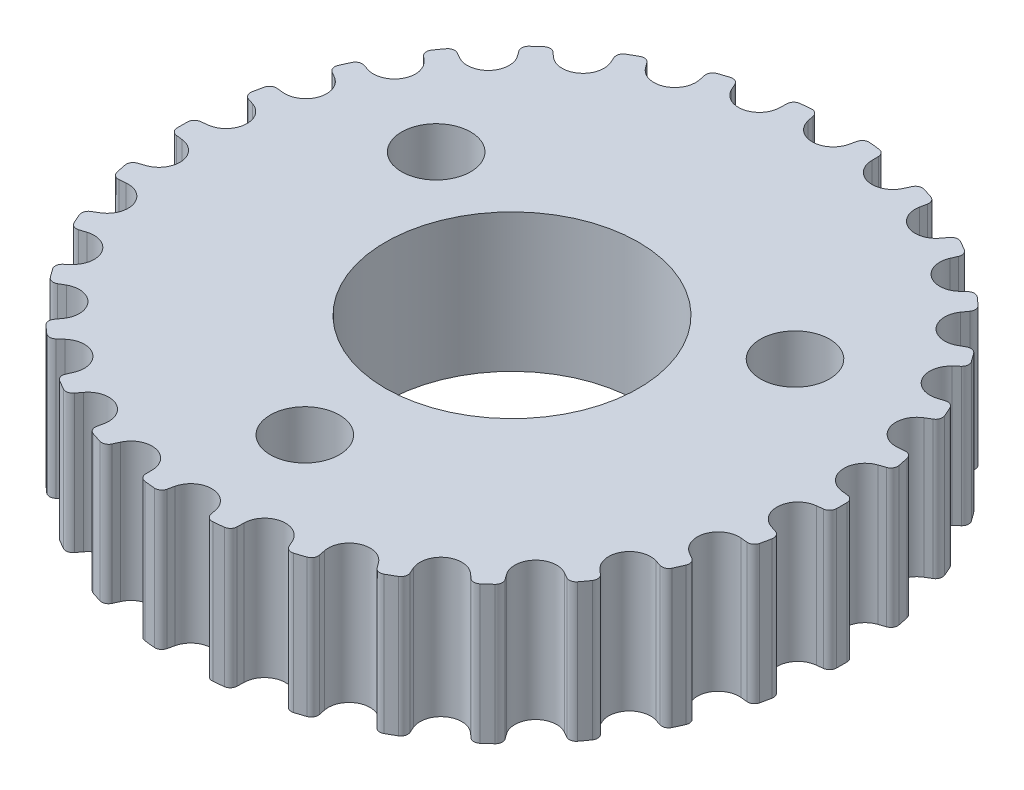
SolidWorks part; units mm, degrees
material "Acrylic (Medium-high impact)"
ref_plane "Front Plane" through (0, 0, 0) normal (0, 0, 1) x (1, 0, 0)
ref_plane "Top Plane" through (0, 0, 0) normal (0, 1, 0) x (1, 0, 0)
ref_plane "Right Plane" through (0, 0, 0) normal (1, 0, 0) x (0, 0, -1)
sketch "Sketch1" plane through (0, 0, 0) normal (0, 1, 0) x (1, 0, 0)
  circle A0 centre (0, 0) radius 14.3239
  dimension "D1" = 28.6479
extrude "Boss-Extrude1" add sketch "Sketch1" along normal blind 6
sketch "Sketch2" plane through (0, 6, 0) normal (0, 1, 0) x (1, 0, 0)
  line L0 (0, 0) -> (0, 14.3239) construction
  line L1 (-0.8883, 13.7564) -> (-0.95, 14.0339)
  line L2 (-2.9781, 14.0109) -> (-2.9781, 14.3239)
  line L3 (-2.9781, 14.3239) -> (2.9781, 14.3239)
  line L4 (0.8883, 13.7564) -> (0.95, 14.0339)
  line L5 (2.9781, 14.0109) -> (2.9781, 14.3239)
  circle A0 centre (0, 0) radius 14.3239 construction
  arc A1 (0.8883, 13.7564) -> (-0.8883, 13.7564) centre (0, 13.9539) cw
  arc A2 (-0.95, 14.0339) -> (-1.2694, 14.2676) centre (-1.2428, 13.9688) ccw
  arc A4 (0.95, 14.0339) -> (1.2694, 14.2676) centre (1.2428, 13.9688) cw
  arc A5 (-1.2694, 14.2676) -> (-2.9781, 14.0109) centre (0, 0) ccw
  arc A6 (1.2694, 14.2676) -> (2.9781, 14.0109) centre (0, 0) cw
  circle A8 centre (0, 0) radius 14.3239 construction
  point P11 (0, 14.3239)
  point P19 (0, 13.0439)
  dimension "D3" = 0.3
  dimension "D5" = 0.91
  dimension "D2" = 0.95
  dimension "D4" = 1.28
  dimension "D6" = 12
extrude "Cut-Extrude1" cut sketch "Sketch2" against normal through all
pattern_circular "CirPattern1" count 30 over 360 about axis through (0, 0, 0) along (0, 1, 0) of "Cut-Extrude1"
sketch "Sketch3" plane through (0, 0, 0) normal (0, -1, 0) x (1, 0, 0)
  circle A0 centre (0, 0) radius 5.5
  dimension "D1" = 11
extrude "Cut-Extrude2" cut sketch "Sketch3" against normal through all
sketch "Sketch4" plane through (0, 0, 0) normal (0, -1, 0) x (1, 0, 0)
  line L0 (0, 0) -> (0, 9) construction
  circle A0 centre (0, 9) radius 1.5
  circle A1 centre (7.7942, -4.5) radius 1.5
  circle A2 centre (-7.7942, -4.5) radius 1.5
  point P14 (0, 0)
  dimension "D1" = 3
  dimension "D2" = 9
  dimension "D3" = 3
extrude "Cut-Extrude3" cut sketch "Sketch4" against normal through all
sketch "Sketch5" plane through (0, 0, 0) normal (0, -1, 0) x (1, 0, 0)
  line L60 (8.7383, -10.682) -> (8.9513, -10.8702)
  line L61 (8.7383, -10.682) -> (8.9513, -10.8702)
  line L62 (9.875, -10.0385) -> (9.7101, -9.807)
  line L63 (9.875, -10.0385) -> (9.7101, -9.807)
  line L64 (12.5987, 6.2896) -> (12.3276, 6.2043)
  line L65 (12.5987, 6.2896) -> (12.3276, 6.2043)
  line L66 (11.5369, 7.5738) -> (11.7463, 7.766)
  line L67 (11.5369, 7.5738) -> (11.7463, 7.766)
  line L68 (-3.638, 13.3126) -> (-3.7561, 13.5712)
  line L69 (-3.638, 13.3126) -> (-3.7561, 13.5712)
  line L70 (-4.9382, 13.1871) -> (-4.8817, 12.9085)
  line L71 (-4.9382, 13.1871) -> (-4.8817, 12.9085)
  line L72 (-11.7463, 7.766) -> (-11.5369, 7.5738)
  line L73 (-11.7463, 7.766) -> (-11.5369, 7.5738)
  line L74 (-12.3276, 6.2043) -> (-12.5987, 6.2896)
  line L75 (-12.3276, 6.2043) -> (-12.5987, 6.2896)
  line L76 (-13.1043, 5.1541) -> (-12.8594, 5.0097)
  line L77 (-13.1043, 5.1541) -> (-12.8594, 5.0097)
  line L78 (-13.3481, 3.5057) -> (-13.6311, 3.5327)
  line L79 (-13.3481, 3.5057) -> (-13.6311, 3.5327)
  line L80 (-13.8895, 2.3169) -> (-13.62, 2.2266)
  line L81 (-13.8895, 2.3169) -> (-13.62, 2.2266)
  line L82 (-13.7853, 0.6538) -> (-14.0677, 0.6215)
  line L83 (-13.7853, 0.6538) -> (-14.0677, 0.6215)
  line L84 (-14.0677, -0.6215) -> (-13.7853, -0.6538)
  line L85 (-14.0677, -0.6215) -> (-13.7853, -0.6538)
  line L86 (-13.62, -2.2266) -> (-13.8895, -2.3169)
  line L87 (-13.62, -2.2266) -> (-13.8895, -2.3169)
  line L88 (-13.6311, -3.5327) -> (-13.3481, -3.5057)
  line L89 (-13.6311, -3.5327) -> (-13.3481, -3.5057)
  line L90 (-12.8594, -5.0097) -> (-13.1043, -5.1541)
  line L91 (-12.8594, -5.0097) -> (-13.1043, -5.1541)
  line L92 (-12.5987, -6.2896) -> (-12.3276, -6.2043)
  line L93 (-12.5987, -6.2896) -> (-12.3276, -6.2043)
  line L94 (-11.5369, -7.5738) -> (-11.7463, -7.766)
  line L95 (-11.5369, -7.5738) -> (-11.7463, -7.766)
  line L96 (-11.0157, -8.7716) -> (-10.7682, -8.6318)
  line L97 (-11.0157, -8.7716) -> (-10.7682, -8.6318)
  line L98 (-9.7101, -9.807) -> (-9.875, -10.0385)
  line L99 (-9.7101, -9.807) -> (-9.875, -10.0385)
  line L100 (-8.9513, -10.8702) -> (-8.7383, -10.682)
  line L101 (-8.9513, -10.8702) -> (-8.7383, -10.682)
  line L102 (-7.4589, -11.6115) -> (-7.5721, -11.8722)
  line L103 (-7.4589, -11.6115) -> (-7.5721, -11.8722)
  line L104 (-6.4956, -12.4937) -> (-6.3264, -12.2653)
  line L105 (-6.4956, -12.4937) -> (-6.3264, -12.2653)
  line L106 (-4.8817, -12.9085) -> (-4.9382, -13.1871)
  line L107 (-4.8817, -12.9085) -> (-4.9382, -13.1871)
  line L108 (-3.7561, -13.5712) -> (-3.638, -13.3126)
  line L109 (-3.7561, -13.5712) -> (-3.638, -13.3126)
  line L110 (-2.0912, -13.6414) -> (-2.0886, -13.9257)
  line L111 (-2.0912, -13.6414) -> (-2.0886, -13.9257)
  line L120 (6.3264, -12.2653) -> (6.4956, -12.4937)
  line L121 (7.5721, -11.8722) -> (7.4589, -11.6115)
  line L124 (10.7682, -8.6318) -> (11.0157, -8.7716)
  line L125 (11.7463, -7.766) -> (11.5369, -7.5738)
  line L126 (12.3276, -6.2043) -> (12.5987, -6.2896)
  line L127 (13.1043, -5.1541) -> (12.8594, -5.0097)
  line L128 (13.3481, -3.5057) -> (13.6311, -3.5327)
  line L129 (13.8895, -2.3169) -> (13.62, -2.2266)
  line L130 (13.7853, -0.6538) -> (14.0677, -0.6215)
  line L131 (14.0677, 0.6215) -> (13.7853, 0.6538)
  line L132 (13.62, 2.2266) -> (13.8895, 2.3169)
  line L133 (13.6311, 3.5327) -> (13.3481, 3.5057)
  line L134 (12.8594, 5.0097) -> (13.1043, 5.1541)
  line L137 (11.0157, 8.7716) -> (10.7682, 8.6318)
  line L138 (9.7101, 9.807) -> (9.875, 10.0385)
  line L139 (8.9513, 10.8702) -> (8.7383, 10.682)
  line L140 (7.4589, 11.6115) -> (7.5721, 11.8722)
  line L141 (6.4956, 12.4937) -> (6.3264, 12.2653)
  line L142 (4.8817, 12.9085) -> (4.9382, 13.1871)
  line L143 (3.7561, 13.5712) -> (3.638, 13.3126)
  line L144 (2.0912, 13.6414) -> (2.0886, 13.9257)
  line L145 (0.8524, 14.0556) -> (0.7907, 13.7781)
  line L146 (-0.7907, 13.7781) -> (-0.8524, 14.0556)
  line L147 (-2.0886, 13.9257) -> (-2.0912, 13.6414)
  line L150 (-6.3264, 12.2653) -> (-6.4956, 12.4937)
  line L151 (-7.5721, 11.8722) -> (-7.4589, 11.6115)
  line L152 (-8.7383, 10.682) -> (-8.9513, 10.8702)
  line L153 (-9.875, 10.0385) -> (-9.7101, 9.807)
  line L154 (-10.7682, 8.6318) -> (-11.0157, 8.7716)
  line L175 (-0.8524, -14.0556) -> (-0.7907, -13.7781)
  line L176 (0.7907, -13.7781) -> (0.8524, -14.0556)
  line L177 (2.0886, -13.9257) -> (2.0912, -13.6414)
  line L178 (3.638, -13.3126) -> (3.7561, -13.5712)
  line L179 (4.9382, -13.1871) -> (4.8817, -12.9085)
  line L180 (6.3264, -12.2653) -> (6.4956, -12.4937)
  line L181 (7.5721, -11.8722) -> (7.4589, -11.6115)
  line L184 (10.7682, -8.6318) -> (11.0157, -8.7716)
  line L185 (11.7463, -7.766) -> (11.5369, -7.5738)
  line L186 (12.3276, -6.2043) -> (12.5987, -6.2896)
  line L187 (13.1043, -5.1541) -> (12.8594, -5.0097)
  line L188 (13.3481, -3.5057) -> (13.6311, -3.5327)
  line L189 (13.8895, -2.3169) -> (13.62, -2.2266)
  line L190 (13.7853, -0.6538) -> (14.0677, -0.6215)
  line L191 (14.0677, 0.6215) -> (13.7853, 0.6538)
  line L192 (13.62, 2.2266) -> (13.8895, 2.3169)
  line L193 (13.6311, 3.5327) -> (13.3481, 3.5057)
  line L194 (12.8594, 5.0097) -> (13.1043, 5.1541)
  line L197 (11.0157, 8.7716) -> (10.7682, 8.6318)
  line L198 (9.7101, 9.807) -> (9.875, 10.0385)
  line L199 (8.9513, 10.8702) -> (8.7383, 10.682)
  line L200 (7.4589, 11.6115) -> (7.5721, 11.8722)
  line L201 (6.4956, 12.4937) -> (6.3264, 12.2653)
  line L202 (4.8817, 12.9085) -> (4.9382, 13.1871)
  line L203 (3.7561, 13.5712) -> (3.638, 13.3126)
  line L204 (2.0912, 13.6414) -> (2.0886, 13.9257)
  line L205 (0.8524, 14.0556) -> (0.7907, 13.7781)
  line L206 (-0.7907, 13.7781) -> (-0.8524, 14.0556)
  line L207 (-2.0886, 13.9257) -> (-2.0912, 13.6414)
  line L210 (-6.3264, 12.2653) -> (-6.4956, 12.4937)
  line L211 (-7.5721, 11.8722) -> (-7.4589, 11.6115)
  line L212 (-8.7383, 10.682) -> (-8.9513, 10.8702)
  line L213 (-9.875, 10.0385) -> (-9.7101, 9.807)
  line L214 (-10.7682, 8.6318) -> (-11.0157, 8.7716)
  line L235 (-0.8524, -14.0556) -> (-0.7907, -13.7781)
  line L236 (0.7907, -13.7781) -> (0.8524, -14.0556)
  line L237 (2.0886, -13.9257) -> (2.0912, -13.6414)
  line L238 (3.638, -13.3126) -> (3.7561, -13.5712)
  line L239 (4.9382, -13.1871) -> (4.8817, -12.9085)
  arc A76 (8.9513, -10.8702) -> (9.479, -10.8719) centre (9.2161, -10.5704) ccw
  arc A77 (8.9513, -10.8702) -> (9.479, -10.8719) centre (9.2161, -10.5704) ccw
  arc A78 (9.479, -10.8719) -> (9.8216, -10.5635) centre (0, 0) ccw
  arc A79 (9.479, -10.8719) -> (9.8216, -10.5635) centre (0, 0) ccw
  arc A80 (9.8216, -10.5635) -> (9.875, -10.0385) centre (9.5492, -10.2705) ccw
  arc A81 (9.8216, -10.5635) -> (9.875, -10.0385) centre (9.5492, -10.2705) ccw
  circle A120 centre (0, 0) radius 13.0439
  arc A121 (-0.8883, 13.7564) -> (0.8883, 13.7564) centre (0, 13.9539) ccw construction
  arc A128 (11.5369, 7.5738) -> (12.3276, 6.2043) centre (12.0845, 6.977) ccw
  arc A129 (11.5369, 7.5738) -> (12.3276, 6.2043) centre (12.0845, 6.977) ccw
  arc A130 (-3.7561, 13.5712) -> (-4.2375, 13.7875) centre (-4.12, 13.4051) ccw
  arc A131 (-3.7561, 13.5712) -> (-4.2375, 13.7875) centre (-4.12, 13.4051) ccw
  arc A132 (-4.2375, 13.7875) -> (-4.6759, 13.645) centre (0, 0) ccw
  arc A133 (-4.2375, 13.7875) -> (-4.6759, 13.645) centre (0, 0) ccw
  arc A134 (-4.6759, 13.645) -> (-4.9382, 13.1871) centre (-4.5462, 13.2666) ccw
  arc A135 (-4.6759, 13.645) -> (-4.9382, 13.1871) centre (-4.5462, 13.2666) ccw
  arc A136 (-11.8032, 8.2906) -> (-11.7463, 7.766) centre (-11.4759, 8.0607) ccw
  arc A137 (-11.8032, 8.2906) -> (-11.7463, 7.766) centre (-11.4759, 8.0607) ccw
  arc A138 (-12.3276, 6.2043) -> (-11.5369, 7.5738) centre (-12.0845, 6.977) ccw
  arc A139 (-12.3276, 6.2043) -> (-11.5369, 7.5738) centre (-12.0845, 6.977) ccw
  arc A140 (-12.5987, 6.2896) -> (-13.0815, 6.0766) centre (-12.7187, 5.908) ccw
  arc A141 (-12.5987, 6.2896) -> (-13.0815, 6.0766) centre (-12.7187, 5.908) ccw
  arc A142 (-13.0815, 6.0766) -> (-13.269, 5.6554) centre (0, 0) ccw
  arc A143 (-13.0815, 6.0766) -> (-13.269, 5.6554) centre (0, 0) ccw
  arc A144 (-13.269, 5.6554) -> (-13.1043, 5.1541) centre (-12.901, 5.4986) ccw
  arc A145 (-13.269, 5.6554) -> (-13.1043, 5.1541) centre (-12.901, 5.4986) ccw
  arc A146 (-13.3481, 3.5057) -> (-12.8594, 5.0097) centre (-13.271, 4.312) ccw
  arc A147 (-13.3481, 3.5057) -> (-12.8594, 5.0097) centre (-13.271, 4.312) ccw
  arc A148 (-13.6311, 3.5327) -> (-14.059, 3.224) centre (-13.6691, 3.1346) ccw
  arc A149 (-13.6311, 3.5327) -> (-14.059, 3.224) centre (-13.6691, 3.1346) ccw
  arc A150 (-14.059, 3.224) -> (-14.1549, 2.7731) centre (0, 0) ccw
  arc A151 (-14.059, 3.224) -> (-14.1549, 2.7731) centre (0, 0) ccw
  arc A152 (-14.1549, 2.7731) -> (-13.8895, 2.3169) centre (-13.7623, 2.6962) ccw
  arc A153 (-14.1549, 2.7731) -> (-13.8895, 2.3169) centre (-13.7623, 2.6962) ccw
  arc A154 (-13.7853, 0.6538) -> (-13.62, 2.2266) centre (-13.8775, 1.4586) ccw
  arc A155 (-13.7853, 0.6538) -> (-13.62, 2.2266) centre (-13.8775, 1.4586) ccw
  arc A156 (-14.0677, 0.6215) -> (-14.4221, 0.2305) centre (-14.0222, 0.2241) ccw
  arc A157 (-14.0677, 0.6215) -> (-14.4221, 0.2305) centre (-14.0222, 0.2241) ccw
  arc A158 (-14.4221, 0.2305) -> (-14.4221, -0.2305) centre (0, 0) ccw
  arc A159 (-14.4221, 0.2305) -> (-14.4221, -0.2305) centre (0, 0) ccw
  arc A160 (-14.4221, -0.2305) -> (-14.0677, -0.6215) centre (-14.0222, -0.2241) ccw
  arc A161 (-14.4221, -0.2305) -> (-14.0677, -0.6215) centre (-14.0222, -0.2241) ccw
  arc A162 (-13.62, -2.2266) -> (-13.7853, -0.6538) centre (-13.8775, -1.4586) ccw
  arc A163 (-13.62, -2.2266) -> (-13.7853, -0.6538) centre (-13.8775, -1.4586) ccw
  arc A164 (-13.8895, -2.3169) -> (-14.1549, -2.7731) centre (-13.7623, -2.6962) ccw
  arc A165 (-13.8895, -2.3169) -> (-14.1549, -2.7731) centre (-13.7623, -2.6962) ccw
  arc A166 (-14.1549, -2.7731) -> (-14.059, -3.224) centre (0, 0) ccw
  arc A167 (-14.1549, -2.7731) -> (-14.059, -3.224) centre (0, 0) ccw
  arc A168 (-14.059, -3.224) -> (-13.6311, -3.5327) centre (-13.6691, -3.1346) ccw
  arc A169 (-14.059, -3.224) -> (-13.6311, -3.5327) centre (-13.6691, -3.1346) ccw
  arc A170 (-12.8594, -5.0097) -> (-13.3481, -3.5057) centre (-13.271, -4.312) ccw
  arc A171 (-12.8594, -5.0097) -> (-13.3481, -3.5057) centre (-13.271, -4.312) ccw
  arc A172 (-13.1043, -5.1541) -> (-13.269, -5.6554) centre (-12.901, -5.4986) ccw
  arc A173 (-13.1043, -5.1541) -> (-13.269, -5.6554) centre (-12.901, -5.4986) ccw
  arc A174 (-13.269, -5.6554) -> (-13.0815, -6.0766) centre (0, 0) ccw
  arc A175 (-13.269, -5.6554) -> (-13.0815, -6.0766) centre (0, 0) ccw
  arc A176 (-13.0815, -6.0766) -> (-12.5987, -6.2896) centre (-12.7187, -5.908) ccw
  arc A177 (-13.0815, -6.0766) -> (-12.5987, -6.2896) centre (-12.7187, -5.908) ccw
  arc A178 (-11.5369, -7.5738) -> (-12.3276, -6.2043) centre (-12.0845, -6.977) ccw
  arc A179 (-11.5369, -7.5738) -> (-12.3276, -6.2043) centre (-12.0845, -6.977) ccw
  arc A180 (-11.7463, -7.766) -> (-11.8032, -8.2906) centre (-11.4759, -8.0607) ccw
  arc A181 (-11.7463, -7.766) -> (-11.8032, -8.2906) centre (-11.4759, -8.0607) ccw
  arc A182 (-11.8032, -8.2906) -> (-11.5323, -8.6636) centre (0, 0) ccw
  arc A183 (-11.8032, -8.2906) -> (-11.5323, -8.6636) centre (0, 0) ccw
  arc A184 (-11.5323, -8.6636) -> (-11.0157, -8.7716) centre (-11.2124, -8.4233) ccw
  arc A185 (-11.5323, -8.6636) -> (-11.0157, -8.7716) centre (-11.2124, -8.4233) ccw
  arc A186 (-9.7101, -9.807) -> (-10.7682, -8.6318) centre (-10.3698, -9.337) ccw
  arc A187 (-9.7101, -9.807) -> (-10.7682, -8.6318) centre (-10.3698, -9.337) ccw
  arc A188 (-9.875, -10.0385) -> (-9.8216, -10.5635) centre (-9.5492, -10.2705) ccw
  arc A189 (-9.875, -10.0385) -> (-9.8216, -10.5635) centre (-9.5492, -10.2705) ccw
  arc A190 (-9.8216, -10.5635) -> (-9.479, -10.8719) centre (0, 0) ccw
  arc A191 (-9.8216, -10.5635) -> (-9.479, -10.8719) centre (0, 0) ccw
  arc A192 (-9.479, -10.8719) -> (-8.9513, -10.8702) centre (-9.2161, -10.5704) ccw
  arc A193 (-9.479, -10.8719) -> (-8.9513, -10.8702) centre (-9.2161, -10.5704) ccw
  arc A194 (-7.4589, -11.6115) -> (-8.7383, -10.682) centre (-8.2019, -11.289) ccw
  arc A195 (-7.4589, -11.6115) -> (-8.7383, -10.682) centre (-8.2019, -11.289) ccw
  arc A196 (-7.5721, -11.8722) -> (-7.4107, -12.3747) centre (-7.2051, -12.0315) ccw
  arc A197 (-7.5721, -11.8722) -> (-7.4107, -12.3747) centre (-7.2051, -12.0315) ccw
  arc A198 (-7.4107, -12.3747) -> (-7.0114, -12.6052) centre (0, 0) ccw
  arc A199 (-7.4107, -12.3747) -> (-7.0114, -12.6052) centre (0, 0) ccw
  arc A200 (-7.0114, -12.6052) -> (-6.4956, -12.4937) centre (-6.817, -12.2556) ccw
  arc A201 (-7.0114, -12.6052) -> (-6.4956, -12.4937) centre (-6.817, -12.2556) ccw
  arc A202 (-4.8817, -12.9085) -> (-6.3264, -12.2653) centre (-5.6756, -12.7476) ccw
  arc A203 (-4.8817, -12.9085) -> (-6.3264, -12.2653) centre (-5.6756, -12.7476) ccw
  arc A204 (-4.9382, -13.1871) -> (-4.6759, -13.645) centre (-4.5462, -13.2666) ccw
  arc A205 (-4.9382, -13.1871) -> (-4.6759, -13.645) centre (-4.5462, -13.2666) ccw
  arc A206 (-4.6759, -13.645) -> (-4.2375, -13.7875) centre (0, 0) ccw
  arc A207 (-4.6759, -13.645) -> (-4.2375, -13.7875) centre (0, 0) ccw
  arc A208 (-4.2375, -13.7875) -> (-3.7561, -13.5712) centre (-4.12, -13.4051) ccw
  arc A209 (-4.2375, -13.7875) -> (-3.7561, -13.5712) centre (-4.12, -13.4051) ccw
  arc A210 (-2.0912, -13.6414) -> (-3.638, -13.3126) centre (-2.9012, -13.649) ccw
  arc A211 (-2.0912, -13.6414) -> (-3.638, -13.3126) centre (-2.9012, -13.649) ccw
  arc A212 (-2.0886, -13.9257) -> (-1.7367, -14.319) centre (-1.6886, -13.9219) ccw
  arc A213 (-2.0886, -13.9257) -> (-1.7367, -14.319) centre (-1.6886, -13.9219) ccw
  arc A214 (-1.7367, -14.319) -> (-1.2783, -14.3672) centre (0, 0) ccw
  arc A215 (-1.7367, -14.319) -> (-1.2783, -14.3672) centre (0, 0) ccw
  arc A240 (6.4956, -12.4937) -> (7.0114, -12.6052) centre (6.817, -12.2556) ccw
  arc A241 (7.0114, -12.6052) -> (7.4107, -12.3747) centre (0, 0) ccw
  arc A242 (7.4107, -12.3747) -> (7.5721, -11.8722) centre (7.2051, -12.0315) ccw
  arc A243 (8.7383, -10.682) -> (7.4589, -11.6115) centre (8.2019, -11.289) ccw
  arc A247 (10.7682, -8.6318) -> (9.7101, -9.807) centre (10.3698, -9.337) ccw
  arc A248 (11.0157, -8.7716) -> (11.5323, -8.6636) centre (11.2124, -8.4233) ccw
  arc A249 (11.5323, -8.6636) -> (11.8032, -8.2906) centre (0, 0) ccw
  arc A250 (11.8032, -8.2906) -> (11.7463, -7.766) centre (11.4759, -8.0607) ccw
  arc A251 (12.3276, -6.2043) -> (11.5369, -7.5738) centre (12.0845, -6.977) ccw
  arc A252 (12.5987, -6.2896) -> (13.0815, -6.0766) centre (12.7187, -5.908) ccw
  arc A253 (13.0815, -6.0766) -> (13.269, -5.6554) centre (0, 0) ccw
  arc A254 (13.269, -5.6554) -> (13.1043, -5.1541) centre (12.901, -5.4986) ccw
  arc A255 (13.3481, -3.5057) -> (12.8594, -5.0097) centre (13.271, -4.312) ccw
  arc A256 (13.6311, -3.5327) -> (14.059, -3.224) centre (13.6691, -3.1346) ccw
  arc A257 (14.059, -3.224) -> (14.1549, -2.7731) centre (0, 0) ccw
  arc A258 (14.1549, -2.7731) -> (13.8895, -2.3169) centre (13.7623, -2.6962) ccw
  arc A259 (13.7853, -0.6538) -> (13.62, -2.2266) centre (13.8775, -1.4586) ccw
  arc A260 (14.0677, -0.6215) -> (14.4221, -0.2305) centre (14.0222, -0.2241) ccw
  arc A261 (14.4221, -0.2305) -> (14.4221, 0.2305) centre (0, 0) ccw
  arc A262 (14.4221, 0.2305) -> (14.0677, 0.6215) centre (14.0222, 0.2241) ccw
  arc A263 (13.62, 2.2266) -> (13.7853, 0.6538) centre (13.8775, 1.4586) ccw
  arc A264 (13.8895, 2.3169) -> (14.1549, 2.7731) centre (13.7623, 2.6962) ccw
  arc A265 (14.1549, 2.7731) -> (14.059, 3.224) centre (0, 0) ccw
  arc A266 (14.059, 3.224) -> (13.6311, 3.5327) centre (13.6691, 3.1346) ccw
  arc A267 (12.8594, 5.0097) -> (13.3481, 3.5057) centre (13.271, 4.312) ccw
  arc A268 (13.1043, 5.1541) -> (13.269, 5.6554) centre (12.901, 5.4986) ccw
  arc A269 (13.269, 5.6554) -> (13.0815, 6.0766) centre (0, 0) ccw
  arc A270 (13.0815, 6.0766) -> (12.5987, 6.2896) centre (12.7187, 5.908) ccw
  arc A272 (11.7463, 7.766) -> (11.8032, 8.2906) centre (11.4759, 8.0607) ccw
  arc A273 (11.8032, 8.2906) -> (11.5323, 8.6636) centre (0, 0) ccw
  arc A274 (11.5323, 8.6636) -> (11.0157, 8.7716) centre (11.2124, 8.4233) ccw
  arc A275 (9.7101, 9.807) -> (10.7682, 8.6318) centre (10.3698, 9.337) ccw
  arc A276 (9.875, 10.0385) -> (9.8216, 10.5635) centre (9.5492, 10.2705) ccw
  arc A277 (9.8216, 10.5635) -> (9.479, 10.8719) centre (0, 0) ccw
  arc A278 (9.479, 10.8719) -> (8.9513, 10.8702) centre (9.2161, 10.5704) ccw
  arc A279 (7.4589, 11.6115) -> (8.7383, 10.682) centre (8.2019, 11.289) ccw
  arc A280 (7.5721, 11.8722) -> (7.4107, 12.3747) centre (7.2051, 12.0315) ccw
  arc A281 (7.4107, 12.3747) -> (7.0114, 12.6052) centre (0, 0) ccw
  arc A282 (7.0114, 12.6052) -> (6.4956, 12.4937) centre (6.817, 12.2556) ccw
  arc A283 (4.8817, 12.9085) -> (6.3264, 12.2653) centre (5.6756, 12.7476) ccw
  arc A284 (4.9382, 13.1871) -> (4.6759, 13.645) centre (4.5462, 13.2666) ccw
  arc A285 (4.6759, 13.645) -> (4.2375, 13.7875) centre (0, 0) ccw
  arc A286 (4.2375, 13.7875) -> (3.7561, 13.5712) centre (4.12, 13.4051) ccw
  arc A287 (2.0912, 13.6414) -> (3.638, 13.3126) centre (2.9012, 13.649) ccw
  arc A288 (2.0886, 13.9257) -> (1.7367, 14.319) centre (1.6886, 13.9219) ccw
  arc A289 (1.7367, 14.319) -> (1.2783, 14.3672) centre (0, 0) ccw
  arc A290 (1.2783, 14.3672) -> (0.8524, 14.0556) centre (1.2428, 13.9688) ccw
  arc A291 (-0.7907, 13.7781) -> (0.7907, 13.7781) centre (0, 13.9539) ccw
  arc A292 (-0.8524, 14.0556) -> (-1.2783, 14.3672) centre (-1.2428, 13.9688) ccw
  arc A293 (-1.2783, 14.3672) -> (-1.7367, 14.319) centre (0, 0) ccw
  arc A294 (-1.7367, 14.319) -> (-2.0886, 13.9257) centre (-1.6886, 13.9219) ccw
  arc A295 (-3.638, 13.3126) -> (-2.0912, 13.6414) centre (-2.9012, 13.649) ccw
  arc A299 (-6.3264, 12.2653) -> (-4.8817, 12.9085) centre (-5.6756, 12.7476) ccw
  arc A300 (-6.4956, 12.4937) -> (-7.0114, 12.6052) centre (-6.817, 12.2556) ccw
  arc A301 (-7.0114, 12.6052) -> (-7.4107, 12.3747) centre (0, 0) ccw
  arc A302 (-7.4107, 12.3747) -> (-7.5721, 11.8722) centre (-7.2051, 12.0315) ccw
  arc A303 (-8.7383, 10.682) -> (-7.4589, 11.6115) centre (-8.2019, 11.289) ccw
  arc A304 (-8.9513, 10.8702) -> (-9.479, 10.8719) centre (-9.2161, 10.5704) ccw
  arc A305 (-9.479, 10.8719) -> (-9.8216, 10.5635) centre (0, 0) ccw
  arc A306 (-9.8216, 10.5635) -> (-9.875, 10.0385) centre (-9.5492, 10.2705) ccw
  arc A307 (-10.7682, 8.6318) -> (-9.7101, 9.807) centre (-10.3698, 9.337) ccw
  arc A308 (-11.0157, 8.7716) -> (-11.5323, 8.6636) centre (-11.2124, 8.4233) ccw
  arc A309 (-11.5323, 8.6636) -> (-11.8032, 8.2906) centre (0, 0) ccw
  arc A350 (-1.2783, -14.3672) -> (-0.8524, -14.0556) centre (-1.2428, -13.9688) ccw
  arc A351 (0.7907, -13.7781) -> (-0.7907, -13.7781) centre (0, -13.9539) ccw
  arc A352 (0.8524, -14.0556) -> (1.2783, -14.3672) centre (1.2428, -13.9688) ccw
  arc A353 (1.2783, -14.3672) -> (1.7367, -14.319) centre (0, 0) ccw
  arc A354 (1.7367, -14.319) -> (2.0886, -13.9257) centre (1.6886, -13.9219) ccw
  arc A355 (3.638, -13.3126) -> (2.0912, -13.6414) centre (2.9012, -13.649) ccw
  arc A356 (3.7561, -13.5712) -> (4.2375, -13.7875) centre (4.12, -13.4051) ccw
  arc A357 (4.2375, -13.7875) -> (4.6759, -13.645) centre (0, 0) ccw
  arc A358 (4.6759, -13.645) -> (4.9382, -13.1871) centre (4.5462, -13.2666) ccw
  arc A359 (6.3264, -12.2653) -> (4.8817, -12.9085) centre (5.6756, -12.7476) ccw
  arc A360 (6.4956, -12.4937) -> (7.0114, -12.6052) centre (6.817, -12.2556) ccw
  arc A361 (7.0114, -12.6052) -> (7.4107, -12.3747) centre (0, 0) ccw
  arc A362 (7.4107, -12.3747) -> (7.5721, -11.8722) centre (7.2051, -12.0315) ccw
  arc A363 (8.7383, -10.682) -> (7.4589, -11.6115) centre (8.2019, -11.289) ccw
  arc A367 (10.7682, -8.6318) -> (9.7101, -9.807) centre (10.3698, -9.337) ccw
  arc A368 (11.0157, -8.7716) -> (11.5323, -8.6636) centre (11.2124, -8.4233) ccw
  arc A369 (11.5323, -8.6636) -> (11.8032, -8.2906) centre (0, 0) ccw
  arc A370 (11.8032, -8.2906) -> (11.7463, -7.766) centre (11.4759, -8.0607) ccw
  arc A371 (12.3276, -6.2043) -> (11.5369, -7.5738) centre (12.0845, -6.977) ccw
  arc A372 (12.5987, -6.2896) -> (13.0815, -6.0766) centre (12.7187, -5.908) ccw
  arc A373 (13.0815, -6.0766) -> (13.269, -5.6554) centre (0, 0) ccw
  arc A374 (13.269, -5.6554) -> (13.1043, -5.1541) centre (12.901, -5.4986) ccw
  arc A375 (13.3481, -3.5057) -> (12.8594, -5.0097) centre (13.271, -4.312) ccw
  arc A376 (13.6311, -3.5327) -> (14.059, -3.224) centre (13.6691, -3.1346) ccw
  arc A377 (14.059, -3.224) -> (14.1549, -2.7731) centre (0, 0) ccw
  arc A378 (14.1549, -2.7731) -> (13.8895, -2.3169) centre (13.7623, -2.6962) ccw
  arc A379 (13.7853, -0.6538) -> (13.62, -2.2266) centre (13.8775, -1.4586) ccw
  arc A380 (14.0677, -0.6215) -> (14.4221, -0.2305) centre (14.0222, -0.2241) ccw
  arc A381 (14.4221, -0.2305) -> (14.4221, 0.2305) centre (0, 0) ccw
  arc A382 (14.4221, 0.2305) -> (14.0677, 0.6215) centre (14.0222, 0.2241) ccw
  arc A383 (13.62, 2.2266) -> (13.7853, 0.6538) centre (13.8775, 1.4586) ccw
  arc A384 (13.8895, 2.3169) -> (14.1549, 2.7731) centre (13.7623, 2.6962) ccw
  arc A385 (14.1549, 2.7731) -> (14.059, 3.224) centre (0, 0) ccw
  arc A386 (14.059, 3.224) -> (13.6311, 3.5327) centre (13.6691, 3.1346) ccw
  arc A387 (12.8594, 5.0097) -> (13.3481, 3.5057) centre (13.271, 4.312) ccw
  arc A388 (13.1043, 5.1541) -> (13.269, 5.6554) centre (12.901, 5.4986) ccw
  arc A389 (13.269, 5.6554) -> (13.0815, 6.0766) centre (0, 0) ccw
  arc A390 (13.0815, 6.0766) -> (12.5987, 6.2896) centre (12.7187, 5.908) ccw
  arc A392 (11.7463, 7.766) -> (11.8032, 8.2906) centre (11.4759, 8.0607) ccw
  arc A393 (11.8032, 8.2906) -> (11.5323, 8.6636) centre (0, 0) ccw
  arc A394 (11.5323, 8.6636) -> (11.0157, 8.7716) centre (11.2124, 8.4233) ccw
  arc A395 (9.7101, 9.807) -> (10.7682, 8.6318) centre (10.3698, 9.337) ccw
  arc A396 (9.875, 10.0385) -> (9.8216, 10.5635) centre (9.5492, 10.2705) ccw
  arc A397 (9.8216, 10.5635) -> (9.479, 10.8719) centre (0, 0) ccw
  arc A398 (9.479, 10.8719) -> (8.9513, 10.8702) centre (9.2161, 10.5704) ccw
  arc A399 (7.4589, 11.6115) -> (8.7383, 10.682) centre (8.2019, 11.289) ccw
  arc A400 (7.5721, 11.8722) -> (7.4107, 12.3747) centre (7.2051, 12.0315) ccw
  arc A401 (7.4107, 12.3747) -> (7.0114, 12.6052) centre (0, 0) ccw
  arc A402 (7.0114, 12.6052) -> (6.4956, 12.4937) centre (6.817, 12.2556) ccw
  arc A403 (4.8817, 12.9085) -> (6.3264, 12.2653) centre (5.6756, 12.7476) ccw
  arc A404 (4.9382, 13.1871) -> (4.6759, 13.645) centre (4.5462, 13.2666) ccw
  arc A405 (4.6759, 13.645) -> (4.2375, 13.7875) centre (0, 0) ccw
  arc A406 (4.2375, 13.7875) -> (3.7561, 13.5712) centre (4.12, 13.4051) ccw
  arc A407 (2.0912, 13.6414) -> (3.638, 13.3126) centre (2.9012, 13.649) ccw
  arc A408 (2.0886, 13.9257) -> (1.7367, 14.319) centre (1.6886, 13.9219) ccw
  arc A409 (1.7367, 14.319) -> (1.2783, 14.3672) centre (0, 0) ccw
  arc A410 (1.2783, 14.3672) -> (0.8524, 14.0556) centre (1.2428, 13.9688) ccw
  arc A411 (-0.7907, 13.7781) -> (0.7907, 13.7781) centre (0, 13.9539) ccw
  arc A412 (-0.8524, 14.0556) -> (-1.2783, 14.3672) centre (-1.2428, 13.9688) ccw
  arc A413 (-1.2783, 14.3672) -> (-1.7367, 14.319) centre (0, 0) ccw
  arc A414 (-1.7367, 14.319) -> (-2.0886, 13.9257) centre (-1.6886, 13.9219) ccw
  arc A415 (-3.638, 13.3126) -> (-2.0912, 13.6414) centre (-2.9012, 13.649) ccw
  arc A419 (-6.3264, 12.2653) -> (-4.8817, 12.9085) centre (-5.6756, 12.7476) ccw
  arc A420 (-6.4956, 12.4937) -> (-7.0114, 12.6052) centre (-6.817, 12.2556) ccw
  arc A421 (-7.0114, 12.6052) -> (-7.4107, 12.3747) centre (0, 0) ccw
  arc A422 (-7.4107, 12.3747) -> (-7.5721, 11.8722) centre (-7.2051, 12.0315) ccw
  arc A423 (-8.7383, 10.682) -> (-7.4589, 11.6115) centre (-8.2019, 11.289) ccw
  arc A424 (-8.9513, 10.8702) -> (-9.479, 10.8719) centre (-9.2161, 10.5704) ccw
  arc A425 (-9.479, 10.8719) -> (-9.8216, 10.5635) centre (0, 0) ccw
  arc A426 (-9.8216, 10.5635) -> (-9.875, 10.0385) centre (-9.5492, 10.2705) ccw
  arc A427 (-10.7682, 8.6318) -> (-9.7101, 9.807) centre (-10.3698, 9.337) ccw
  arc A428 (-11.0157, 8.7716) -> (-11.5323, 8.6636) centre (-11.2124, 8.4233) ccw
  arc A429 (-11.5323, 8.6636) -> (-11.8032, 8.2906) centre (0, 0) ccw
  arc A470 (-1.2783, -14.3672) -> (-0.8524, -14.0556) centre (-1.2428, -13.9688) ccw
  arc A471 (0.7907, -13.7781) -> (-0.7907, -13.7781) centre (0, -13.9539) ccw
  arc A472 (0.8524, -14.0556) -> (1.2783, -14.3672) centre (1.2428, -13.9688) ccw
  arc A473 (1.2783, -14.3672) -> (1.7367, -14.319) centre (0, 0) ccw
  arc A474 (1.7367, -14.319) -> (2.0886, -13.9257) centre (1.6886, -13.9219) ccw
  arc A475 (3.638, -13.3126) -> (2.0912, -13.6414) centre (2.9012, -13.649) ccw
  arc A476 (3.7561, -13.5712) -> (4.2375, -13.7875) centre (4.12, -13.4051) ccw
  arc A477 (4.2375, -13.7875) -> (4.6759, -13.645) centre (0, 0) ccw
  arc A478 (4.6759, -13.645) -> (4.9382, -13.1871) centre (4.5462, -13.2666) ccw
  arc A479 (6.3264, -12.2653) -> (4.8817, -12.9085) centre (5.6756, -12.7476) ccw
  dimension "D1" = 0.1
extrude "Boss-Extrude2" [suppressed] add sketch "Sketch5" against normal up to surface (5.8 mm away)
equation "\"smallPulleyTeeth\"= 15"
equation "\"largePulleyTeeth\"= 30"
equation "\"eighthThick\"= 3.0mm"
equation "\"D1@Sketch1\"=3*\"largePulleyTeeth\"/pi"
equation "\"D1@Boss-Extrude1\" = \"eighthThick\" * 2"
equation "\"D6@Sketch2\"=360/\"largePulleyTeeth\""
equation "\"quarterThick\"=6.0mm"
equation "\"D1@CirPattern1\"=\"largePulleyTeeth\""
equation "\"sixteenthThick\"= 1.7mm"
equation "\"OD\"= 145mm"
equation "\"puckAngle\"= 60.5deg"
equation "\"puckDiam\"= 76.5mm"
equation "\"axlePress\"= 5.9mm"
equation "\"press\"= 0.2mm"
equation "\"wheelClear\"= 0.3mm"
equation "\"10-32clear\"= 4.8mm"
equation "\"D1@Sketch4\"=\"4-40clear\""
equation "\"6-32clear\"= 3.3mm"
equation "\"8-32clear\"= 4.0mm"
equation "\"4-40clear\"= 3.0mm"
equation "\"wheelHeight\"= 22mm"
equation "\"wheelWell\"= 65mm"
